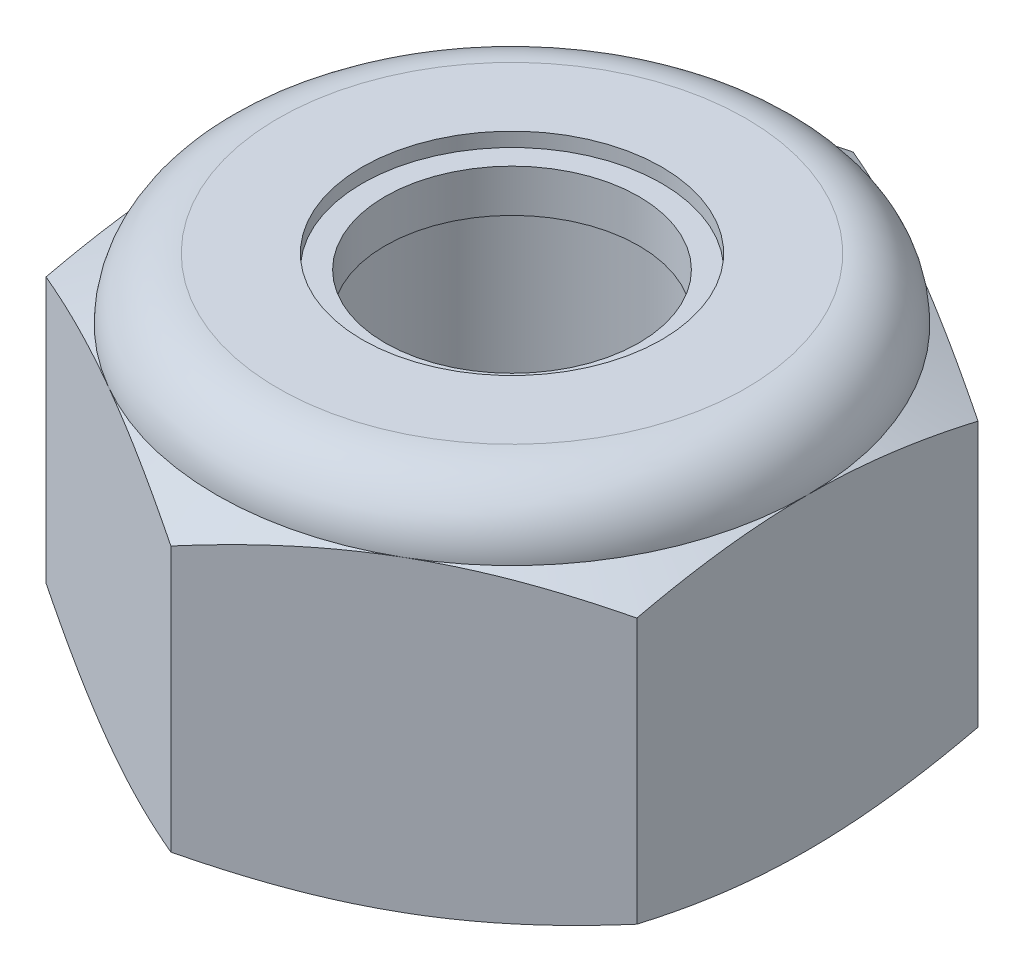
SolidWorks part; units mm, degrees
ref_plane "Front" through (0, 0, 0) normal (0, 0, 1) x (1, 0, 0)
ref_plane "Top" through (0, 0, 0) normal (0, 1, 0) x (1, 0, 0)
ref_plane "Right" through (0, 0, 0) normal (1, 0, 0) x (0, 0, -1)
sketch "Sketch1" plane through (0, 0, 0) normal (0, 1, 0) x (1, 0, 0)
  line L1 (0, 5.4993) -> (-4.7625, 2.7496)
  line L2 (-4.7625, 2.7496) -> (-4.7625, -2.7496)
  line L3 (-4.7625, -2.7496) -> (0, -5.4993)
  line L4 (0, -5.4993) -> (4.7625, -2.7496)
  line L5 (4.7625, -2.7496) -> (4.7625, 2.7496)
  line L6 (4.7625, 2.7496) -> (0, 5.4993)
  circle A0 centre (0, 0) radius 4.7625 construction
  dimension "Hex Flats" = 9.525
extrude "Extrude1" add sketch "Sketch1" along normal blind 5.9531
sketch "Sketch2" plane through (0, 0, 0) normal (1, 0, 0) x (0, 0, -1)
  line L0 (-2.413, 0) -> (-2.413, 5.9531) construction
  line L1 (0, 0) -> (2.413, 0)
  line L2 (0, 0) -> (0, 5.9531)
  line L3 (0, 5.9531) -> (2.413, 5.9531)
  line L4 (2.413, 0) -> (2.413, 5.9531)
  line L5 (-2.7496, 5.9531) -> (2.7496, 5.9531) construction
  line L7 (0, -2.413) -> (0, 0) construction
  dimension "Thread Dia" = 4.826
revolve "Revolve1" add sketch "Sketch2" angle 360 about L7
sketch "Sketch3" plane through (0, 0, 0) normal (1, 0, 0) x (0, 0, -1)
  line L0 (2.413, 5.9531) -> (-2.413, 5.9531) construction
  line L1 (-2.413, 5.9531) -> (-2.413, 5.1594) construction
  line L2 (-2.413, 5.1594) -> (2.413, 5.9531) construction
  line L3 (2.413, 5.9531) -> (2.4291, 5.8552) construction
  line L4 (2.4291, 5.8552) -> (2.5418, 5.1699)
  line L5 (2.5418, 5.1699) -> (2.0776, 5.3449)
  line L6 (2.0776, 5.3449) -> (2.0454, 5.5407)
  line L7 (2.0454, 5.5407) -> (2.4291, 5.8552)
  line L8 (2.0615, 5.4428) -> (2.4855, 5.5126) construction
  line L9 (2.413, 5.9531) -> (2.413, 5.5006) construction
  line L10 (2.413, 5.5006) -> (-2.413, 4.7069) construction
  line L11 (-2.413, 4.7069) -> (-2.413, 5.1594) construction
  line L12 (-0.1397, 5.9531) -> (0.1397, 4.2544) construction
  line L13 (-2.413, 0) -> (-2.413, 5.9531) construction
  line L14 (0, 5.9531) -> (2.413, 5.9531) construction
  line L15 (2.413, 0) -> (2.413, 5.9531) construction
  point P13 (0, 5.1038)
  dimension "D1" = 0.0992
  dimension "D2" = 0.1984
  dimension "Thread Pitch" = 0.7937
  dimension "D4" = 60
  dimension "D5" = 0.7937
revolve "Cut-Revolve1" [suppressed] cut sketch "Sketch3" angle 360 about L12
pattern_linear "LPattern1" [suppressed] count 8 spacing 0.7937 along (0, 1, 0) count 2 spacing 0.7937 along (0, 1, 0)
sketch "Sketch4" plane through (0, 0, 0) normal (1, 0, 0) x (0, 0, -1)
  line L0 (0, 5.9531) -> (2.413, 5.9531)
  line L1 (2.413, 5.9531) -> (2.0454, 5.7817)
  line L2 (2.0454, 5.7817) -> (2.0454, 0.1714)
  line L3 (2.0454, 0.1714) -> (2.413, 0)
  line L4 (2.413, 0) -> (0, 0)
  line L5 (0, 0) -> (0, 5.9531)
  line L6 (2.413, 0) -> (2.413, 5.9531) construction
  line L7 (0, 5.9531) -> (2.413, 5.9531) construction
  line L8 (0, 0) -> (2.413, 0) construction
  line L9 (0, 0) -> (0, 5.9531) construction
  line L10 (0, 5.9531) -> (0, 6.3587) construction
  dimension "D1" = 25
revolve "Cut-Revolve2" [suppressed] cut sketch "Sketch4" angle 360 about L10
combine bodies "Combine1" operation type subtract main body 108 bodies to subtract 109
sketch "Sketch5" plane through (0, 0, 0) normal (1, 0, 0) x (0, 0, -1)
  line L0 (0, 0) -> (4.7625, 0)
  line L1 (4.7625, 0) -> (5.4993, 0.3436)
  line L2 (5.4993, 0.3436) -> (5.4993, 4.6174)
  line L3 (5.4993, 4.6174) -> (4.7625, 4.9609)
  line L4 (3.7703, 5.9531) -> (3.7703, 7.2231)
  line L5 (3.7703, 7.2231) -> (6.7693, 7.2231)
  line L6 (6.7693, 7.2231) -> (6.7693, -1.27)
  line L7 (6.7693, -1.27) -> (0, -1.27)
  line L8 (0, -1.27) -> (0, 0)
  line L9 (4.7625, 4.9609) -> (4.7625, 0) construction
  line L10 (0, 0) -> (2.413, 0) construction
  line L13 (5.4993, 2.4805) -> (6.7693, 2.4805) construction
  line L14 (5.4993, 5.9531) -> (5.4993, 0) construction
  line L15 (0, 0) -> (0, 7.2231) construction
  line L20 (0, 7.2231) -> (3.7703, 7.2231) construction
  line L22 (0, 5.9531) -> (2.413, 5.9531) construction
  arc A0 (4.7625, 4.9609) -> (3.7703, 5.9531) centre (3.7703, 4.9609) ccw
  dimension "D1" = 25
  dimension "D2" = 1.27
  dimension "D3" = 5.9531
  dimension "D4" = 0.9922
revolve "Cut-Revolve3" cut sketch "Sketch5" angle 360 about L15
sketch "Sketch6" plane through (0, 0, 0) normal (1, 0, 0) x (0, 0, -1)
  line L0 (0, 4.9609) -> (4.6101, 4.9609)
  line L1 (3.7703, 5.8007) -> (2.9079, 5.8007)
  line L2 (0, 7.2231) -> (0, 4.9609)
  line L3 (2.9079, 7.2231) -> (0, 7.2231)
  line L4 (0, 7.2231) -> (3.7703, 7.2231) construction
  line L5 (0, 0) -> (0, 7.2231) construction
  line L6 (0, 7.2231) -> (0, 44.323) construction
  line L7 (2.9079, 5.8007) -> (2.9079, 7.2231)
  line L8 (3.7703, 5.9531) -> (3.7703, 5.8007) construction
  line L9 (2.9079, 5.8007) -> (2.0454, 5.8007) construction
  line L10 (2.0454, 5.8007) -> (2.0454, 5.7817) construction
  arc A0 (4.6101, 4.9609) -> (3.7703, 5.8007) centre (3.7703, 4.9609) ccw
  arc A1 (4.7625, 4.9609) -> (3.7703, 5.9531) centre (3.7703, 4.9609) ccw construction
  dimension "D1" = 0.1524
revolve "Cut-Revolve4" [suppressed] cut sketch "Sketch6" angle 360 about L6
sketch "Sketch7" plane through (0, 0, 0) normal (1, 0, 0) x (0, 0, -1)
  line L0 (2.0454, 5.0371) -> (4.5301, 5.0371)
  line L1 (3.7703, 5.7245) -> (2.0454, 5.7245)
  line L2 (2.0454, 5.7245) -> (2.0454, 5.0371)
  line L3 (2.0454, 5.0371) -> (0, 5.0371) construction
  line L4 (0, 5.0371) -> (0, 5.7245) construction
  line L5 (0, 5.7245) -> (2.0454, 5.7245) construction
  line L6 (2.0454, 5.0371) -> (2.0454, 4.9609) construction
  line L7 (0, 4.9609) -> (4.6101, 4.9609) construction
  line L8 (3.7703, 5.7245) -> (3.7703, 5.8007) construction
  arc A0 (4.5301, 5.0371) -> (3.7703, 5.7245) centre (3.7703, 4.9609) ccw
  arc A2 (4.6101, 4.9609) -> (3.7703, 5.8007) centre (3.7703, 4.9609) ccw construction
  dimension "D1" = 0.0762
revolve "Revolve2" add sketch "Sketch7" angle 360 about L4
other "Freeze***"
equation "\"D1@Sketch3\"=\"Thread Pitch@Sketch3\"/8"
equation "\"D2@Sketch3\"=\"Thread Pitch@Sketch3\"/4"
equation "\"D5@Sketch3\"=\"Thread Pitch@Sketch3\""
equation "\"D4@LPattern1\"=\"Thread Pitch@Sketch3\""
equation "\"D3@LPattern1\"=\"Thread Pitch@Sketch3\""
equation "\"D1@LPattern1\"=\"Height@Extrude1\"/\"Thread Pitch@Sketch3\""
equation "\"D4@Sketch5\"=\"Height@Extrude1\"/6"
